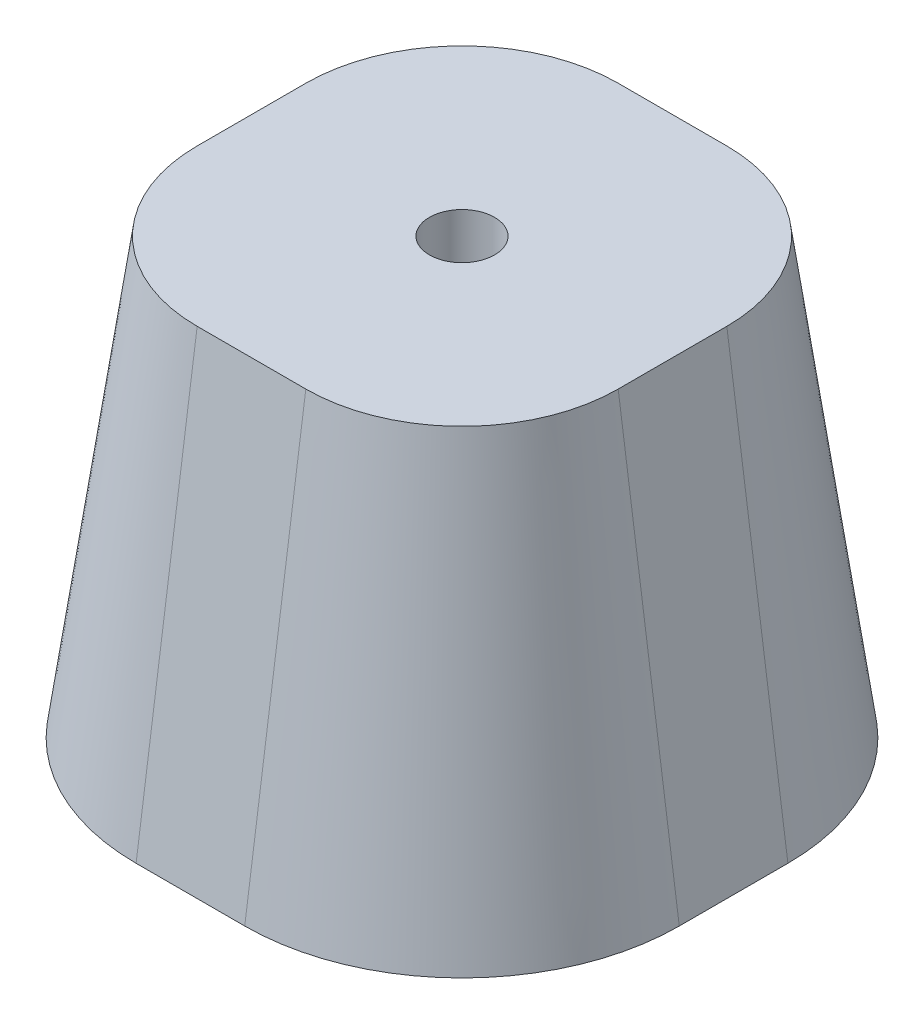
SolidWorks part; units mm, degrees
ref_plane "Front Plane" through (0, 0, 0) normal (0, 0, 1) x (1, 0, 0)
ref_plane "Top Plane" through (0, 0, 0) normal (0, 1, 0) x (1, 0, 0)
ref_plane "Right Plane" through (0, 0, 0) normal (1, 0, 0) x (0, 0, -1)
sketch "Sketch1" plane through (0, 0, 0) normal (0, 1, 0) x (1, 0, 0)
  line L1 (2.5, -12.5) -> (-2.5, -12.5)
  line L2 (12.5, -2.5) -> (12.5, 2.5)
  line L3 (2.5, 12.5) -> (-2.5, 12.5)
  line L4 (-12.5, -2.5) -> (-12.5, 2.5)
  line L5 (12.5, -12.5) -> (-12.5, 12.5) construction
  line L6 (12.5, 12.5) -> (-12.5, -12.5) construction
  arc A1 (-2.5, -12.5) -> (-12.5, -2.5) centre (-2.5, -2.5) cw
  arc A2 (2.5, -12.5) -> (12.5, -2.5) centre (2.5, -2.5) ccw
  arc A3 (12.5, 2.5) -> (2.5, 12.5) centre (2.5, 2.5) ccw
  arc A4 (-12.5, 2.5) -> (-2.5, 12.5) centre (-2.5, 2.5) cw
  point P0 (0, 0)
  dimension "D2" = 10
  dimension "D1" = 25
extrude "Body" add sketch "Sketch1" along normal blind 20 draft 8
sketch "Sketch2" plane through (0, 20, 0) normal (0, 1, 0) x (1, 0, 0)
  circle A0 centre (0, 0) radius 1.5
  dimension "D1" = 3
extrude "Screw" cut sketch "Sketch2" against normal blind 8
equation "\"base\"=25"
equation "\"D1@Sketch1\"=\"base\""
equation "\"draft\"=8"
equation "\"D3@Body\" = \"draft\""
equation "\"screw_hole\"=3"
equation "\"D1@Sketch2\"=\"screw_hole\""
equation "\"screw_depth\"=8"
equation "\"D1@Screw\" = \"screw_depth\""
equation "\"D1@Body\" = \"screw_depth\" * 2"
